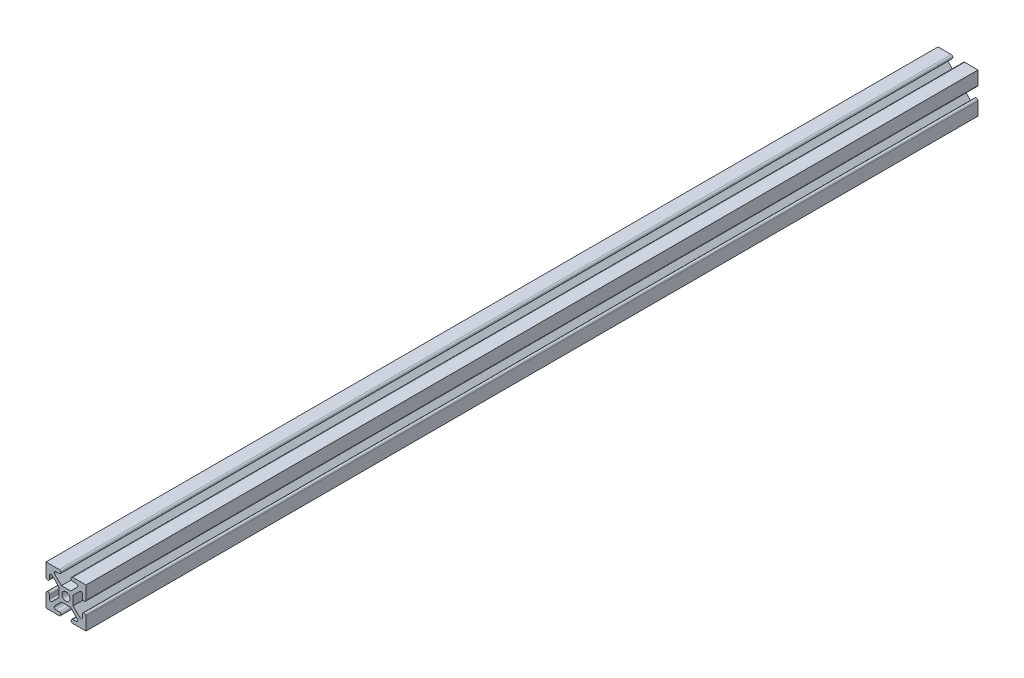
SolidWorks part; units mm, degrees
ref_plane "Front Plane" through (0, 0, 0) normal (0, 0, 1) x (1, 0, 0)
ref_plane "Top Plane" through (0, 0, 0) normal (0, 1, 0) x (1, 0, 0)
ref_plane "Right Plane" through (0, 0, 0) normal (1, 0, 0) x (0, 0, -1)
sketch "Sketch1" plane through (0, 0, 0) normal (0, 0, 1) x (1, 0, 0)
  line L2 (-12.7, -12.7) -> (-4.3434, -12.7)
  line L3 (-4.3434, -10.4902) -> (-6.4748, -10.4902)
  line L4 (-7.1932, -8.7558) -> (-2.9332, -4.4958)
  line L5 (-2.9332, -4.4958) -> (2.9332, -4.4958)
  line L6 (2.9332, -4.4958) -> (7.1932, -8.7558)
  line L7 (6.4748, -10.4902) -> (4.3434, -10.4902)
  line L8 (4.3434, -12.7) -> (12.7, -12.7)
  line L11 (12.7, -12.7) -> (12.7, -4.3434)
  line L12 (10.4902, -4.3434) -> (10.4902, -6.4748)
  line L13 (8.7558, -7.1932) -> (4.4958, -2.9332)
  line L14 (4.4958, -2.9332) -> (4.4958, 2.9332)
  line L15 (4.4958, 2.9332) -> (8.7558, 7.1932)
  line L16 (10.4902, 6.4748) -> (10.4902, 4.3434)
  line L17 (12.7, 4.3434) -> (12.7, 12.7)
  line L20 (12.7, 12.7) -> (4.3434, 12.7)
  line L21 (4.3434, 10.4902) -> (6.4748, 10.4902)
  line L22 (7.1932, 8.7558) -> (2.9332, 4.4958)
  line L23 (2.9332, 4.4958) -> (-2.9332, 4.4958)
  line L24 (-2.9332, 4.4958) -> (-7.1932, 8.7558)
  line L25 (-6.4748, 10.4902) -> (-4.3434, 10.4902)
  line L26 (-4.3434, 12.7) -> (-12.7, 12.7)
  line L29 (-12.7, 12.7) -> (-12.7, 4.3434)
  line L30 (-10.4902, 4.3434) -> (-10.4902, 6.4748)
  line L31 (-8.7558, 7.1932) -> (-4.4958, 2.9332)
  line L32 (-4.4958, 2.9332) -> (-4.4958, -2.9332)
  line L33 (-4.4958, -2.9332) -> (-8.7558, -7.1932)
  line L34 (-10.4902, -6.4748) -> (-10.4902, -4.3434)
  line L35 (-12.7, -4.3434) -> (-12.7, -12.7)
  circle A0 centre (0, 0) radius 2.6035
  arc A6 (-4.3434, -12.7) -> (-4.3434, -10.4902) centre (-4.3434, -11.5951) ccw
  arc A7 (-6.4748, -10.4902) -> (-7.1932, -8.7558) centre (-6.4748, -9.4742) cw
  arc A10 (7.1932, -8.7558) -> (6.4748, -10.4902) centre (6.4748, -9.4742) cw
  arc A11 (4.3434, -10.4902) -> (4.3434, -12.7) centre (4.3434, -11.5951) ccw
  arc A17 (12.7, -4.3434) -> (10.4902, -4.3434) centre (11.5951, -4.3434) ccw
  arc A18 (10.4902, -6.4748) -> (8.7558, -7.1932) centre (9.4742, -6.4748) cw
  arc A21 (8.7558, 7.1932) -> (10.4902, 6.4748) centre (9.4742, 6.4748) cw
  arc A22 (10.4902, 4.3434) -> (12.7, 4.3434) centre (11.5951, 4.3434) ccw
  arc A28 (4.3434, 12.7) -> (4.3434, 10.4902) centre (4.3434, 11.5951) ccw
  arc A29 (6.4748, 10.4902) -> (7.1932, 8.7558) centre (6.4748, 9.4742) cw
  arc A32 (-7.1932, 8.7558) -> (-6.4748, 10.4902) centre (-6.4748, 9.4742) cw
  arc A33 (-4.3434, 10.4902) -> (-4.3434, 12.7) centre (-4.3434, 11.5951) ccw
  arc A39 (-12.7, 4.3434) -> (-10.4902, 4.3434) centre (-11.5951, 4.3434) ccw
  arc A40 (-10.4902, 6.4748) -> (-8.7558, 7.1932) centre (-9.4742, 6.4748) cw
  arc A43 (-8.7558, -7.1932) -> (-10.4902, -6.4748) centre (-9.4742, -6.4748) cw
  arc A44 (-10.4902, -4.3434) -> (-12.7, -4.3434) centre (-11.5951, -4.3434) ccw
  point P101 (-4.4958, 0)
  point P102 (0, 4.4958)
  point P103 (4.4958, 0)
  point P127 (0, -4.4958)
extrude "Boss-Extrude1" add sketch "Sketch1" against normal blind 566.7375
